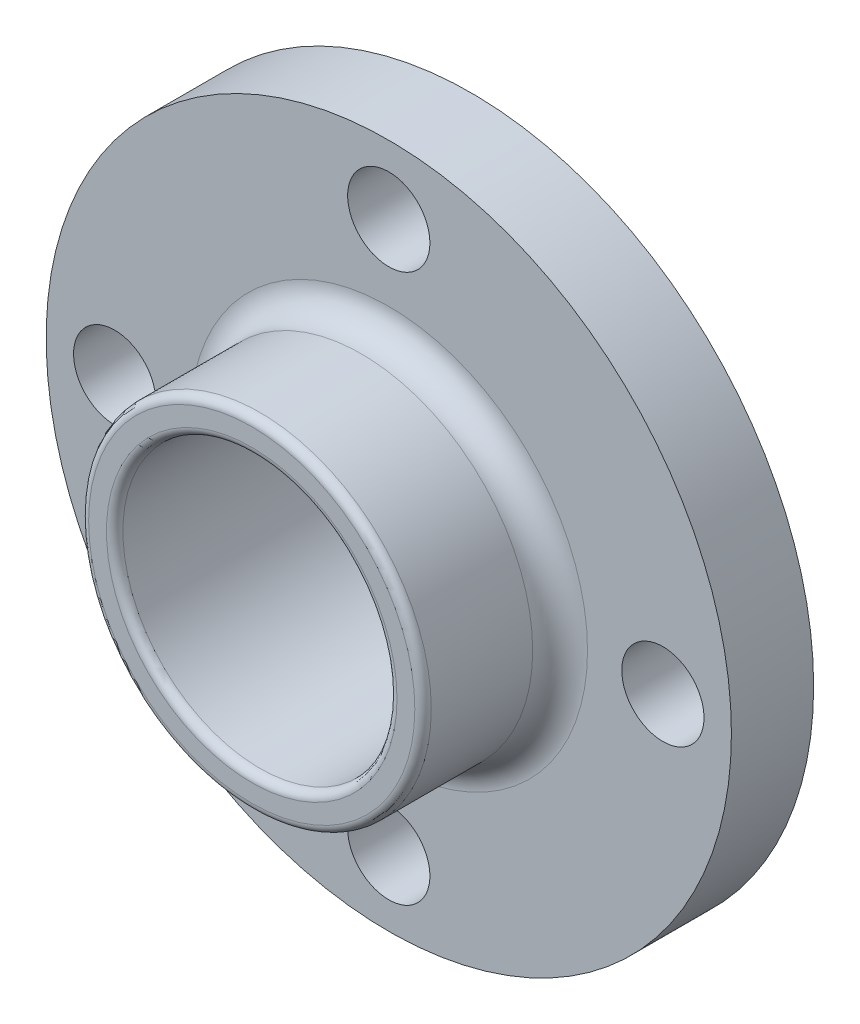
SolidWorks part; units mm, degrees
ref_plane "Front Plane" through (0, 0, 0) normal (0, 0, 1) x (1, 0, 0)
ref_plane "Top Plane" through (0, 0, 0) normal (0, 1, 0) x (1, 0, 0)
ref_plane "Right Plane" through (0, 0, 0) normal (1, 0, 0) x (0, 0, -1)
sketch "Sketch1" plane through (0, 0, 0) normal (0, 0, 1) x (1, 0, 0)
  circle A0 centre (0, 0) radius 1.25
  dimension "D1" = 2.5
extrude "Boss-Extrude1" add sketch "Sketch1" along normal blind 0.3
sketch "Sketch2" plane through (0, 0, 0.3) normal (0, 0, 1) x (1, 0, 0)
  circle A0 centre (0, 0) radius 1
  circle A1 centre (0, 1) radius 0.15
  dimension "D1" = 2
  dimension "D2" = 0.3
extrude "Cut-Extrude1" cut sketch "Sketch2" against normal blind 0.3 contours A1
pattern_circular "CirPattern2" count 4 every 90 about axis through (0, 0, 0) along (0, 0, 1) of "Cut-Extrude1"
sketch "Sketch3" plane through (0, 0, 0.3) normal (0, 0, 1) x (1, 0, 0)
  circle A0 centre (0, 0) radius 0.625
  dimension "D1" = 1.25
extrude "Boss-Extrude2" add sketch "Sketch3" along normal blind 0.5
sketch "Sketch4" plane through (0, 0, 0.8) normal (0, 0, 1) x (1, 0, 0)
  circle A0 centre (0, 0) radius 0.5
  dimension "D1" = 1
extrude "Cut-Extrude3" cut sketch "Sketch4" against normal blind 10.5
fillet "Fillet2" radius 0.1 1 edges at (0.625, 0, 0.3)
fillet "Fillet6" radius 0.03 2 edges at (0.5, 0, 0.8) (0.625, 0, 0.8)
